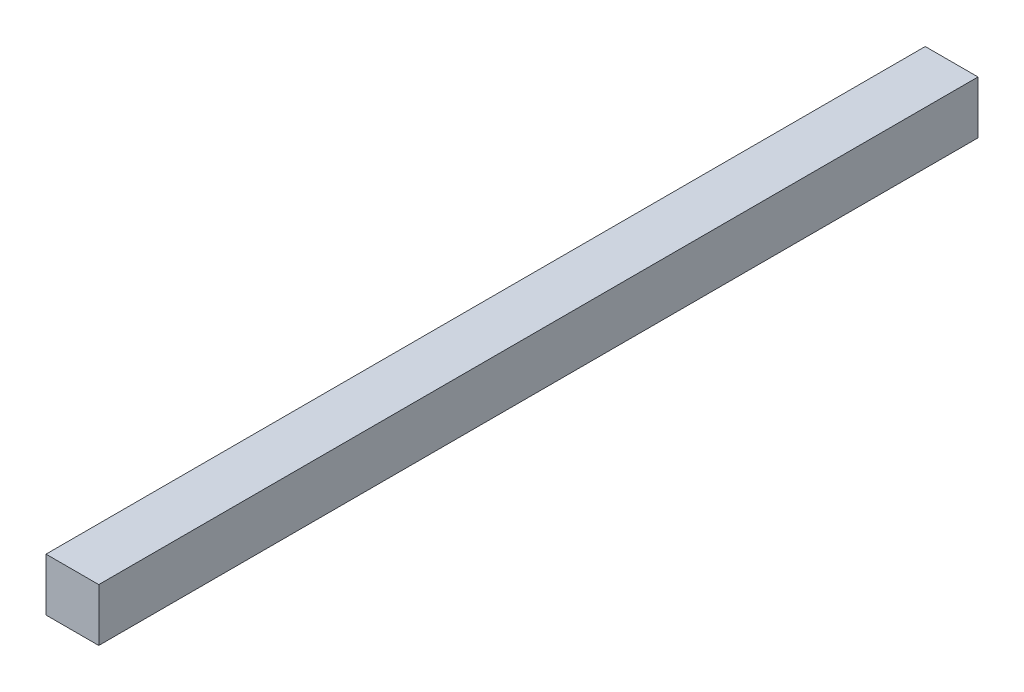
SolidWorks part; units mm, degrees
ref_plane "Front Plane" through (0, 0, 0) normal (0, 0, 1) x (1, 0, 0)
ref_plane "Top Plane" through (0, 0, 0) normal (0, 1, 0) x (1, 0, 0)
ref_plane "Right Plane" through (0, 0, 0) normal (1, 0, 0) x (0, 0, -1)
sketch "Sketch1" plane through (0, 0, 0) normal (0, 0, 1) x (1, 0, 0)
  line L1 (18, -9) -> (0, -9)
  line L2 (18, -9) -> (18, 9)
  line L3 (18, 9) -> (0, 9)
  line L4 (0, -9) -> (0, 9)
  line L5 (18, -9) -> (0, 9) construction
  line L6 (18, 9) -> (0, -9) construction
  point P4 (9, 0)
extrude "Boss-Extrude1" add sketch "Sketch1" along normal up to surface (300 mm away)
